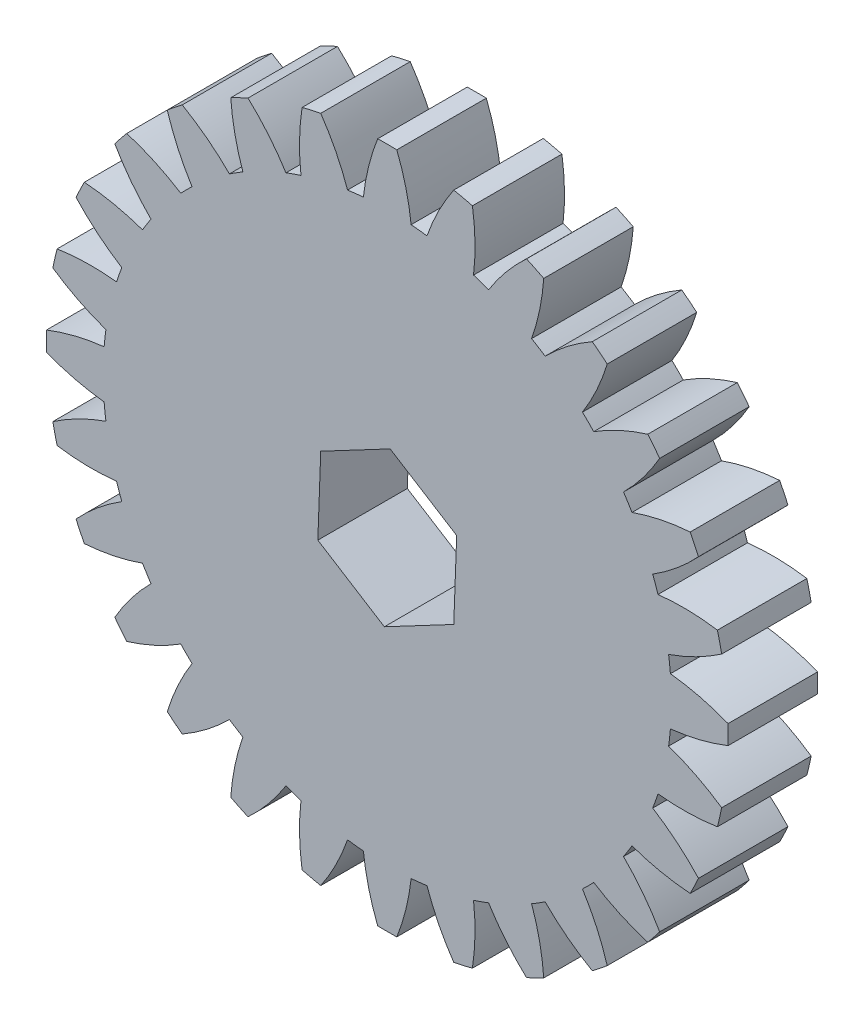
SolidWorks part; units mm, degrees
ref_plane "Front Plane" through (0, 0, 0) normal (0, 0, 1) x (1, 0, 0)
ref_plane "Top Plane" through (0, 0, 0) normal (0, 1, 0) x (1, 0, 0)
ref_plane "Right Plane" through (0, 0, 0) normal (1, 0, 0) x (0, 0, -1)
ref_plane "Plane1" through (0, 0, 5) normal (0, 0, 1) x (1, 0, 0)
sketch "Sketch1" plane through (0, 0, 5) normal (0, 0, 1) x (1, 0, 0)
  line L1 (-3.7162, 2.3331) -> (-3.8786, -2.0517)
  line L2 (-3.8786, -2.0517) -> (-0.1625, -4.3849)
  line L3 (0, 0) -> (-1.7774, 15.7752) construction
  line L4 (-0.1625, -4.3849) -> (3.7162, -2.3331)
  line L5 (3.7162, -2.3331) -> (3.8786, 2.0517)
  line L6 (3.8786, 2.0517) -> (0.1625, 4.3849)
  line L7 (0.1625, 4.3849) -> (-3.7162, 2.3331)
  arc A0 (-4.8209, 15.1253) -> (-5.6614, 14.8312) centre (0, 0) ccw
  arc A1 (-5.6614, 14.8312) -> (-7.7809, 17.3885) centre (-16.2618, 8.2026) ccw
  arc A2 (-7.7809, 17.3885) -> (-8.7436, 16.9249) centre (0, 0) ccw
  arc A3 (-8.7436, 16.9249) -> (-8.0657, 13.6733) centre (3.7261, 17.8282) ccw
  arc A4 (-8.0657, 13.6733) -> (-8.8197, 13.1996) centre (0, 0) ccw
  arc A5 (-8.8197, 13.1996) -> (-11.4551, 15.2211) centre (-17.6794, 4.3783) ccw
  arc A6 (-11.4551, 15.2211) -> (-12.2905, 14.5549) centre (0, 0) ccw
  arc A7 (-12.2905, 14.5549) -> (-10.9061, 11.5357) centre (-0.3345, 18.2104) ccw
  arc A8 (-10.9061, 11.5357) -> (-11.5357, 10.9061) centre (0, 0) ccw
  arc A9 (-11.5357, 10.9061) -> (-14.5549, 12.2905) centre (-18.2104, 0.3345) ccw
  arc A10 (-14.5549, 12.2905) -> (-15.2211, 11.4551) centre (0, 0) ccw
  arc A11 (-15.2211, 11.4551) -> (-13.1996, 8.8197) centre (-4.3783, 17.6794) ccw
  arc A12 (-13.1996, 8.8197) -> (-13.6733, 8.0657) centre (0, 0) ccw
  arc A13 (-13.6733, 8.0657) -> (-16.9249, 8.7436) centre (-17.8282, -3.7261) ccw
  arc A14 (-16.9249, 8.7436) -> (-17.3885, 7.7809) centre (0, 0) ccw
  arc A15 (-17.3885, 7.7809) -> (-14.8312, 5.6614) centre (-8.2026, 16.2618) ccw
  arc A16 (-14.8312, 5.6614) -> (-15.1253, 4.8209) centre (0, 0) ccw
  arc A17 (-15.1253, 4.8209) -> (-18.4462, 4.7582) centre (-16.5521, -7.5998) ccw
  arc A18 (-18.4462, 4.7582) -> (-18.684, 3.7165) centre (0, 0) ccw
  arc A19 (-18.684, 3.7165) -> (-15.7191, 2.2192) centre (-11.6155, 14.0289) ccw
  arc A20 (-15.7191, 2.2192) -> (-15.8188, 1.3343) centre (0, 0) ccw
  arc A21 (-15.8188, 1.3343) -> (-19.0425, 0.5343) centre (-14.446, -11.0924) ccw
  arc A22 (-19.0425, 0.5343) -> (-19.0425, -0.5343) centre (0, 0) ccw
  arc A23 (-19.0425, -0.5343) -> (-15.8188, -1.3343) centre (-14.446, 11.0924) ccw
  arc A24 (-15.8188, -1.3343) -> (-15.7191, -2.2192) centre (0, 0) ccw
  arc A25 (-15.7191, -2.2192) -> (-18.684, -3.7165) centre (-11.6155, -14.0289) ccw
  arc A26 (-18.684, -3.7165) -> (-18.4462, -4.7582) centre (0, 0) ccw
  arc A27 (-18.4462, -4.7582) -> (-15.1253, -4.8209) centre (-16.5521, 7.5998) ccw
  arc A28 (-15.1253, -4.8209) -> (-14.8312, -5.6614) centre (0, 0) ccw
  arc A29 (-14.8312, -5.6614) -> (-17.3885, -7.7809) centre (-8.2026, -16.2618) ccw
  arc A30 (-17.3885, -7.7809) -> (-16.9249, -8.7436) centre (0, 0) ccw
  arc A31 (-16.9249, -8.7436) -> (-13.6733, -8.0657) centre (-17.8282, 3.7261) ccw
  arc A32 (-13.6733, -8.0657) -> (-13.1996, -8.8197) centre (0, 0) ccw
  arc A33 (-13.1996, -8.8197) -> (-15.2211, -11.4551) centre (-4.3783, -17.6794) ccw
  arc A34 (-15.2211, -11.4551) -> (-14.5549, -12.2905) centre (0, 0) ccw
  arc A35 (-14.5549, -12.2905) -> (-11.5357, -10.9061) centre (-18.2104, -0.3345) ccw
  arc A36 (-11.5357, -10.9061) -> (-10.9061, -11.5357) centre (0, 0) ccw
  arc A37 (-10.9061, -11.5357) -> (-12.2905, -14.5549) centre (-0.3345, -18.2104) ccw
  arc A38 (-12.2905, -14.5549) -> (-11.4551, -15.2211) centre (0, 0) ccw
  arc A39 (-11.4551, -15.2211) -> (-8.8197, -13.1996) centre (-17.6794, -4.3783) ccw
  arc A40 (-8.8197, -13.1996) -> (-8.0657, -13.6733) centre (0, 0) ccw
  arc A41 (-8.0657, -13.6733) -> (-8.7436, -16.9249) centre (3.7261, -17.8282) ccw
  arc A42 (-8.7436, -16.9249) -> (-7.7809, -17.3885) centre (0, 0) ccw
  arc A43 (-7.7809, -17.3885) -> (-5.6614, -14.8312) centre (-16.2618, -8.2026) ccw
  arc A44 (-5.6614, -14.8312) -> (-4.8209, -15.1253) centre (0, 0) ccw
  arc A45 (-4.8209, -15.1253) -> (-4.7582, -18.4462) centre (7.5998, -16.5521) ccw
  arc A46 (-4.7582, -18.4462) -> (-3.7165, -18.684) centre (0, 0) ccw
  arc A47 (-3.7165, -18.684) -> (-2.2192, -15.7191) centre (-14.0289, -11.6155) ccw
  arc A48 (-2.2192, -15.7191) -> (-1.3343, -15.8188) centre (0, 0) ccw
  arc A49 (-1.3343, -15.8188) -> (-0.5343, -19.0425) centre (11.0924, -14.446) ccw
  arc A50 (-0.5343, -19.0425) -> (0.5343, -19.0425) centre (0, 0) ccw
  arc A51 (0.5343, -19.0425) -> (1.3343, -15.8188) centre (-11.0924, -14.446) ccw
  arc A52 (1.3343, -15.8188) -> (2.2192, -15.7191) centre (0, 0) ccw
  arc A53 (2.2192, -15.7191) -> (3.7165, -18.684) centre (14.0289, -11.6155) ccw
  arc A54 (3.7165, -18.684) -> (4.7582, -18.4462) centre (0, 0) ccw
  arc A55 (4.7582, -18.4462) -> (4.8209, -15.1253) centre (-7.5998, -16.5521) ccw
  arc A56 (4.8209, -15.1253) -> (5.6614, -14.8312) centre (0, 0) ccw
  arc A57 (5.6614, -14.8312) -> (7.7809, -17.3885) centre (16.2618, -8.2026) ccw
  arc A58 (7.7809, -17.3885) -> (8.7436, -16.9249) centre (0, 0) ccw
  arc A59 (8.7436, -16.9249) -> (8.0657, -13.6733) centre (-3.7261, -17.8282) ccw
  arc A60 (8.0657, -13.6733) -> (8.8197, -13.1996) centre (0, 0) ccw
  arc A61 (8.8197, -13.1996) -> (11.4551, -15.2211) centre (17.6794, -4.3783) ccw
  arc A62 (11.4551, -15.2211) -> (12.2905, -14.5549) centre (0, 0) ccw
  arc A63 (12.2905, -14.5549) -> (10.9061, -11.5357) centre (0.3345, -18.2104) ccw
  arc A64 (10.9061, -11.5357) -> (11.5357, -10.9061) centre (0, 0) ccw
  arc A65 (11.5357, -10.9061) -> (14.5549, -12.2905) centre (18.2104, -0.3345) ccw
  arc A66 (14.5549, -12.2905) -> (15.2211, -11.4551) centre (0, 0) ccw
  arc A67 (15.2211, -11.4551) -> (13.1996, -8.8197) centre (4.3783, -17.6794) ccw
  arc A68 (13.1996, -8.8197) -> (13.6733, -8.0657) centre (0, 0) ccw
  arc A69 (13.6733, -8.0657) -> (16.9249, -8.7436) centre (17.8282, 3.7261) ccw
  arc A70 (16.9249, -8.7436) -> (17.3885, -7.7809) centre (0, 0) ccw
  arc A71 (17.3885, -7.7809) -> (14.8312, -5.6614) centre (8.2026, -16.2618) ccw
  arc A72 (14.8312, -5.6614) -> (15.1253, -4.8209) centre (0, 0) ccw
  arc A73 (15.1253, -4.8209) -> (18.4462, -4.7582) centre (16.5521, 7.5998) ccw
  arc A74 (18.4462, -4.7582) -> (18.684, -3.7165) centre (0, 0) ccw
  arc A75 (18.684, -3.7165) -> (15.7191, -2.2192) centre (11.6155, -14.0289) ccw
  arc A76 (15.7191, -2.2192) -> (15.8188, -1.3343) centre (0, 0) ccw
  arc A77 (15.8188, -1.3343) -> (19.0425, -0.5343) centre (14.446, 11.0924) ccw
  arc A78 (19.0425, -0.5343) -> (19.0425, 0.5343) centre (0, 0) ccw
  arc A79 (19.0425, 0.5343) -> (15.8188, 1.3343) centre (14.446, -11.0924) ccw
  arc A80 (15.8188, 1.3343) -> (15.7191, 2.2192) centre (0, 0) ccw
  arc A81 (15.7191, 2.2192) -> (18.684, 3.7165) centre (11.6155, 14.0289) ccw
  arc A82 (18.684, 3.7165) -> (18.4462, 4.7582) centre (0, 0) ccw
  arc A83 (18.4462, 4.7582) -> (15.1253, 4.8209) centre (16.5521, -7.5998) ccw
  arc A84 (15.1253, 4.8209) -> (14.8312, 5.6614) centre (0, 0) ccw
  arc A85 (14.8312, 5.6614) -> (17.3885, 7.7809) centre (8.2026, 16.2618) ccw
  arc A86 (17.3885, 7.7809) -> (16.9249, 8.7436) centre (0, 0) ccw
  arc A87 (16.9249, 8.7436) -> (13.6733, 8.0657) centre (17.8282, -3.7261) ccw
  arc A88 (13.6733, 8.0657) -> (13.1996, 8.8197) centre (0, 0) ccw
  arc A89 (13.1996, 8.8197) -> (15.2211, 11.4551) centre (4.3783, 17.6794) ccw
  arc A90 (15.2211, 11.4551) -> (14.5549, 12.2905) centre (0, 0) ccw
  arc A91 (14.5549, 12.2905) -> (11.5357, 10.9061) centre (18.2104, 0.3345) ccw
  arc A92 (11.5357, 10.9061) -> (10.9061, 11.5357) centre (0, 0) ccw
  arc A93 (10.9061, 11.5357) -> (12.2905, 14.5549) centre (0.3345, 18.2104) ccw
  arc A94 (12.2905, 14.5549) -> (11.4551, 15.2211) centre (0, 0) ccw
  arc A95 (11.4551, 15.2211) -> (8.8197, 13.1996) centre (17.6794, 4.3783) ccw
  arc A96 (8.8197, 13.1996) -> (8.0657, 13.6733) centre (0, 0) ccw
  arc A97 (8.0657, 13.6733) -> (8.7436, 16.9249) centre (-3.7261, 17.8282) ccw
  arc A98 (8.7436, 16.9249) -> (7.7809, 17.3885) centre (0, 0) ccw
  arc A99 (7.7809, 17.3885) -> (5.6614, 14.8312) centre (16.2618, 8.2026) ccw
  arc A100 (5.6614, 14.8312) -> (4.8209, 15.1253) centre (0, 0) ccw
  arc A101 (4.8209, 15.1253) -> (4.7582, 18.4462) centre (-7.5998, 16.5521) ccw
  arc A102 (4.7582, 18.4462) -> (3.7165, 18.684) centre (0, 0) ccw
  arc A103 (3.7165, 18.684) -> (2.2192, 15.7191) centre (14.0289, 11.6155) ccw
  arc A104 (2.2192, 15.7191) -> (1.3343, 15.8188) centre (0, 0) ccw
  arc A105 (1.3343, 15.8188) -> (0.5343, 19.0425) centre (-11.0924, 14.446) ccw
  arc A106 (0.5343, 19.0425) -> (-0.5343, 19.0425) centre (0, 0) ccw
  arc A107 (-0.5343, 19.0425) -> (-1.3343, 15.8188) centre (11.0924, 14.446) ccw
  arc A108 (-1.3343, 15.8188) -> (-2.2192, 15.7191) centre (0, 0) ccw
  arc A109 (-2.2192, 15.7191) -> (-3.7165, 18.684) centre (-14.0289, 11.6155) ccw
  arc A110 (-3.7165, 18.684) -> (-4.7582, 18.4462) centre (0, 0) ccw
  arc A111 (-4.7582, 18.4462) -> (-4.8209, 15.1253) centre (7.5998, 16.5521) ccw
  circle A112 centre (0, 0) radius 3.8 construction
  dimension "D2" = 7.6
  dimension "D1" = 19.05
extrude "Boss-Extrude1" add sketch "Sketch1" against normal blind 5
